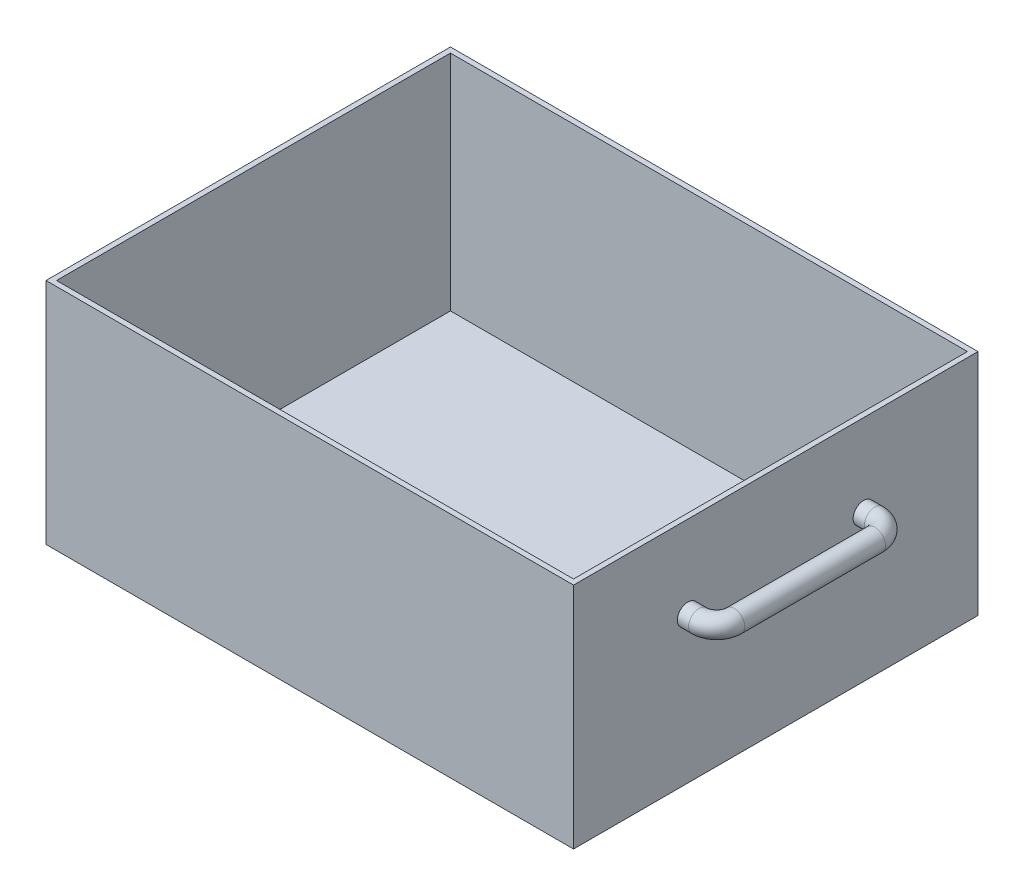
SolidWorks part; units mm, degrees
ref_plane "前视" through (0, 0, 0) normal (0, 0, 1) x (1, 0, 0)
ref_plane "上视" through (0, 0, 0) normal (0, 1, 0) x (1, 0, 0)
ref_plane "右视" through (0, 0, 0) normal (1, 0, 0) x (0, 0, -1)
sketch "Sketch1" plane through (0, 0, 0) normal (0, 1, 0) x (1, 0, 0)
  line L1 (-136.8201, 119.8745) -> (163.1799, 119.8745)
  line L2 (-136.8201, 119.8745) -> (-136.8201, -110.1255)
  line L3 (-136.8201, -110.1255) -> (163.1799, -110.1255)
  line L4 (163.1799, 119.8745) -> (163.1799, -110.1255)
  dimension "D1" = 300
  dimension "D2" = 230
extrude "Boss-Extrude1" add sketch "Sketch1" along normal blind 130
shell "Shell1" thickness 3
sketch "Sketch2" plane through (163.1799, 0, 0) normal (1, 0, 0) x (0, 0, -1)
  line L1 (-110.1255, 130) -> (-110.1255, 0) construction
  circle A0 centre (-45.1255, 83.1724) radius 6
  point P9 (54.8745, 83.1724)
  dimension "D2" = 65
ref_plane "Plane1" through (0, 83.1724, 0) normal (0, 1, 0) x (1, 0, 0)
sketch "Sketch4" plane through (0, 83.1724, 0) normal (0, 1, 0) x (1, 0, 0)
  line L0 (163.1799, -45.1255) -> (169.5656, -45.1255)
  line L1 (179.5656, -35.1255) -> (179.5656, 44.8745)
  line L2 (169.5656, 54.8745) -> (163.1799, 54.8745)
  arc A0 (179.5656, -35.1255) -> (169.5656, -45.1255) centre (169.5656, -35.1255) cw
  arc A1 (179.5656, 44.8745) -> (169.5656, 54.8745) centre (169.5656, 44.8745) ccw
  dimension "D1" = 10
sweep "Sweep2" add profiles "Sketch2" path "Sketch4"
